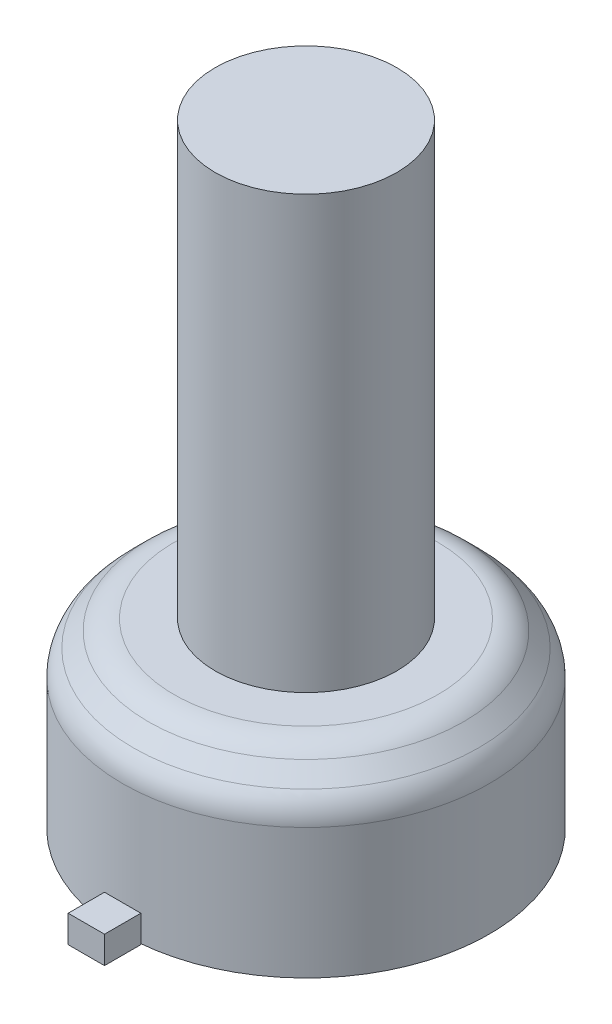
SolidWorks part; units mm, degrees
ref_plane "Front Plane" through (0, 0, 0) normal (0, 0, 1) x (1, 0, 0)
ref_plane "Top Plane" through (0, 0, 0) normal (0, 1, 0) x (1, 0, 0)
ref_plane "Right Plane" through (0, 0, 0) normal (1, 0, 0) x (0, 0, -1)
sketch "Sketch2" plane through (0, 0, 0) normal (0, 1, 0) x (1, 0, 0)
  circle A0 centre (0, 0) radius 5
extrude "Boss-Extrude1" add sketch "Sketch2" along normal blind 23.75
sketch "Sketch3" plane through (0, 0, 0) normal (0, -1, 0) x (1, 0, 0)
  circle A0 centre (0, 0) radius 10.0876
extrude "Boss-Extrude2" add sketch "Sketch3" along normal blind 10
chamfer "Chamfer1" distance 2 angle 45 1 edges at (0, 0, -10.0876)
fillet "Fillet2" radius 2 1 edges at (0, 0, -8.0876)
fillet "Fillet3" radius 2 1 edges at (0, -2, -10.0876)
sketch "Sketch4" plane through (0, 0, 0) normal (1, 0, 0) x (0, 0, -1)
  line L0 (-10.0876, -10) -> (-10.0876, -8.5)
  line L2 (-12.0876, -10) -> (-12.0876, -8.5)
  line L3 (-12.0876, -8.5) -> (-10.0876, -8.5)
  line L6 (-12.0876, -8.5) -> (-10.0876, -10) construction
  line L8 (-10.0876, -10) -> (-12.0876, -10)
  point P0 (-10.0876, -10)
  point P1 (0, 0)
  dimension "D1" = 2
  dimension "D2" = 1.5
extrude "Boss-Extrude3" add sketch "Sketch4" along normal mid plane 2 separate body
